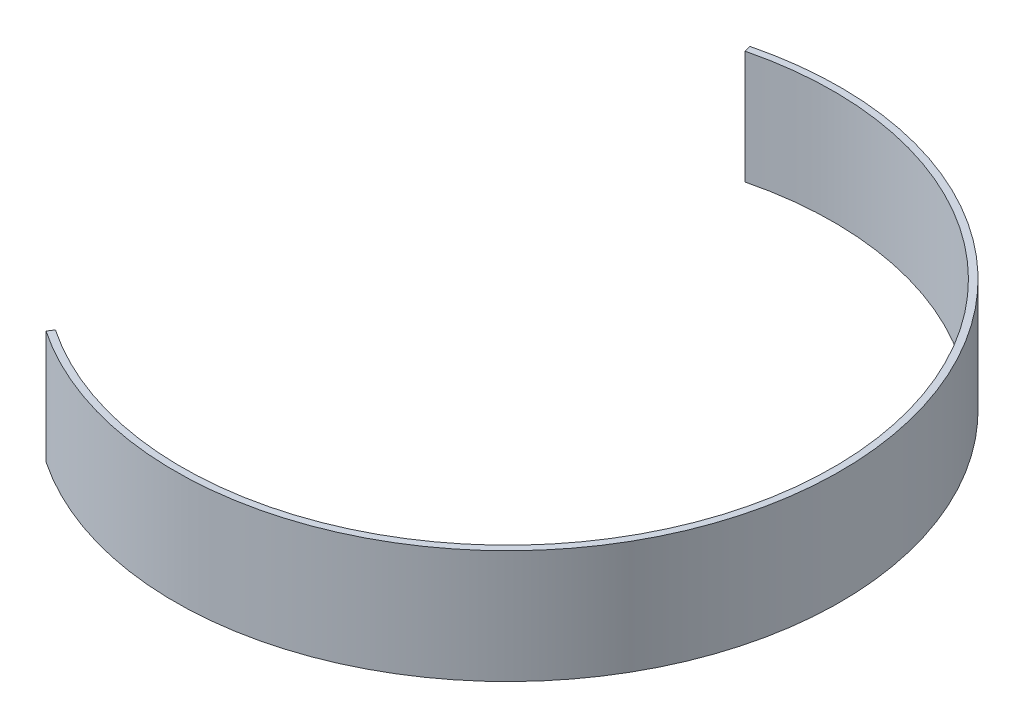
SolidWorks part; units mm, degrees
ref_plane "前视基准面" through (0, 0, 0) normal (0, 0, 1) x (1, 0, 0)
ref_plane "上视基准面" through (0, 0, 0) normal (0, 1, 0) x (1, 0, 0)
ref_plane "右视基准面" through (0, 0, 0) normal (1, 0, 0) x (0, 0, -1)
sketch "草图1" plane through (0, 0, 0) normal (0, 1, 0) x (1, 0, 0)
  line L0 (-57.5, 0) -> (57.5, 0) construction
  line L1 (0, -57.5) -> (0, 57.5) construction
  line L2 (0, 0) -> (-10.9715, 56.4436) construction
  line L3 (-10.9715, 56.4436) -> (-13.9105, 55.792) construction
  line L4 (-13.9105, 55.792) -> (0, 0) construction
  line L5 (0, 0) -> (-32.1536, -47.6697) construction
  line L6 (-14.2008, 56.9564) -> (-13.9105, 55.792)
  line L7 (-32.1536, -47.6697) -> (-32.8246, -48.6645)
  line L8 (0, 0) -> (-7.1537, 58.2625) construction
  line L9 (0, 0) -> (7.1537, 58.2625) construction
  arc A0 (-32.1536, -47.6697) -> (-13.9105, 55.792) centre (0, 0) ccw
  arc A1 (-32.8246, -48.6645) -> (-14.2008, 56.9564) centre (0, 0) ccw
  point P6 (0, 0)
  point P9 (0, 0)
  point P14 (-7.0075, 57.0714)
  point P17 (7.0075, 57.0714)
  dimension "D1" = 115
  dimension "D2" = 11
  dimension "D3" = 14
  dimension "D4" = 34
  dimension "D6" = 7
  dimension "D7" = 7
  dimension "D5" = 1.2
extrude "凸台-拉伸1" add sketch "草图1" along normal blind 20 contours A0 L6 A1 L7
